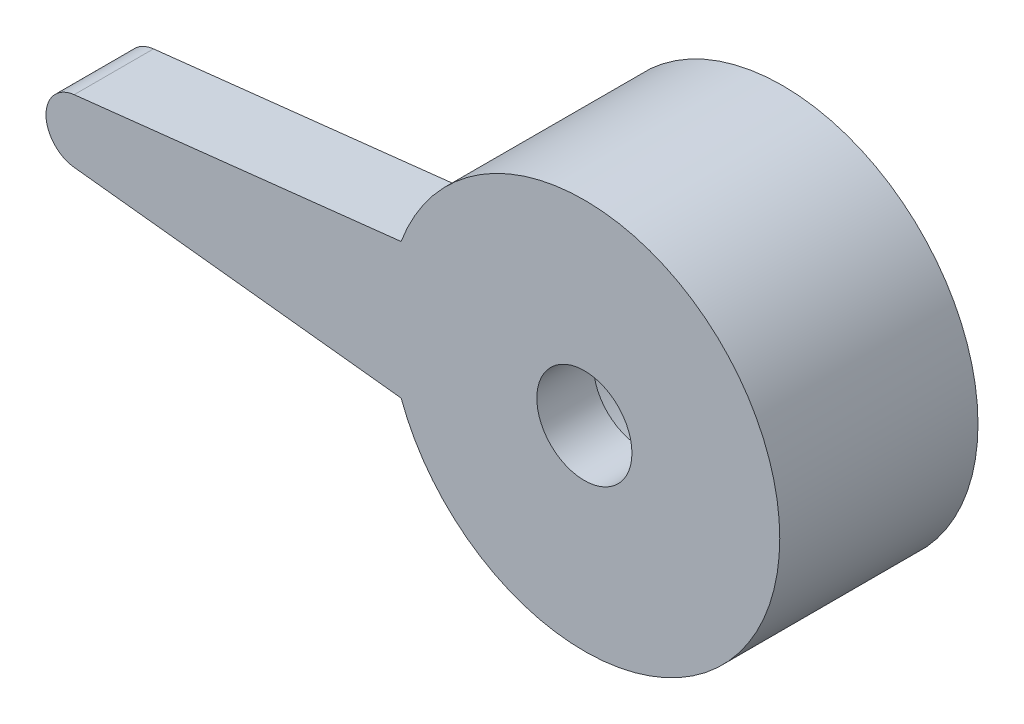
SolidWorks part; units mm, degrees
ref_plane "Front Plane" through (0, 0, 0) normal (0, 0, 1) x (1, 0, 0)
ref_plane "Top Plane" through (0, 0, 0) normal (0, 1, 0) x (1, 0, 0)
ref_plane "Right Plane" through (0, 0, 0) normal (1, 0, 0) x (0, 0, -1)
sketch "outside servo mate" plane through (0, 0, 0) normal (0, 0, 1) x (1, 0, 0)
  circle A0 centre (0, 0) radius 2.45
  dimension "D1" = 4.9
sketch "screw hole" plane through (0, 0, 0) normal (0, 0, 1) x (1, 0, 0)
  circle A0 centre (0, 0) radius 0.84
  dimension "D1" = 1.68
sketch "Sketch7" plane through (0, 0, 0) normal (0, 0, 1) x (1, 0, 0)
  circle A2 centre (0, 0) radius 3.45
  circle A3 centre (0, 0) radius 3.45
extrude "main body" add sketch "Sketch7" against normal blind 3.5
sketch "Sketch9" plane through (0, 0, 0) normal (0, 0, 1) x (1, 0, 0)
  circle A0 centre (0, 0) radius 2.45
  circle A1 centre (0, 0) radius 2.45 construction
extrude "mate hole" cut sketch "Sketch9" against normal up to next from offset 1 offset against normal yes
sketch "Sketch10" plane through (0, 0, 0) normal (0, 0, 1) x (1, 0, 0)
  circle A0 centre (0, 0) radius 0.84
  dimension "D1" = 1.68
extrude "Cut-Extrude2" cut sketch "Sketch10" against normal through all both and the other way through all
sketch "Sketch11" plane through (0, 0, 0) normal (0, 0, 1) x (1, 0, 0)
  line L0 (-3.45, 0) -> (-9.0078, 0) construction
  line L1 (-3.2356, 1.1971) -> (-9.0078, 0.5562)
  line L2 (-9.0078, 0.5562) -> (-9.0078, 0) construction
  line L3 (-3.2356, -1.1971) -> (-9.0078, -0.5562)
  circle A0 centre (0, 0) radius 3.45 construction
  arc A1 (-9.0078, 0.5562) -> (-9.0078, -0.5562) centre (-8.946, 0) ccw
  arc A2 (-3.2356, 1.1971) -> (-3.2356, -1.1971) centre (0, 0) ccw
  point P12 (-3.4138, 1.2631)
extrude "Boss-Extrude2" add sketch "Sketch11" against normal blind 1.4
equation "\"D1@main body\"=\"D1@Sketch7\"+2.5"
equation "\"D19@mate hole\"=\"D1@Sketch7\""
